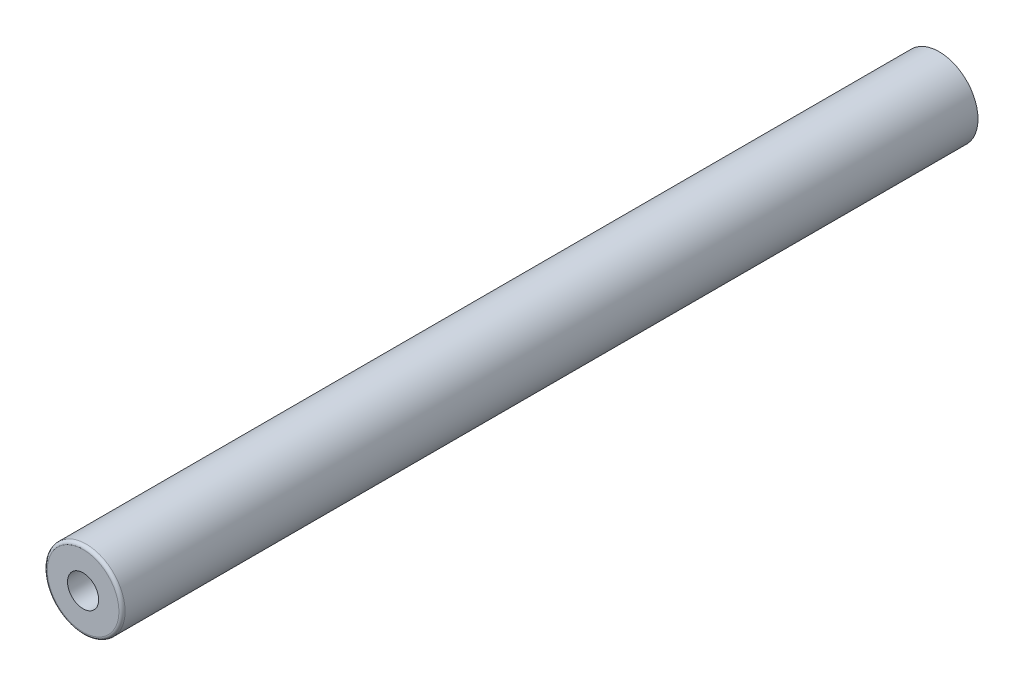
SolidWorks part; units mm, degrees
material "AISI 4130 Steel, normalized at 870C"
ref_plane "Front Plane" through (0, 0, 0) normal (1, 0, 0) x (0, 1, 0)
ref_plane "Top Plane" through (0, 0, 0) normal (0, 0, 1) x (0, 1, 0)
ref_plane "Right Plane" through (0, 0, 0) normal (0, 1, 0) x (-1, 0, 0)
sketch "Sketch1" plane through (0, 0, 0) normal (1, 0, 0) x (0, 1, 0)
  line L0 (0, 319.3174) -> (0, -301.3254) construction
  line L1 (-332.8603, 0) -> (362.1851, 0) construction
  line L2 (10, 275) -> (25, 275)
  line L3 (25, 275) -> (25, -275)
  line L4 (25, -275) -> (20, -275)
  line L5 (10, 235) -> (20, 235)
  line L6 (10, 275) -> (10, 235)
  line L7 (20, 235) -> (20, -275)
  point P13 (25, 0)
  dimension "D1" = 40
  dimension "D2" = 550
  dimension "D3" = 20
  dimension "D4" = 50
  dimension "D5" = 5
revolve "Revolve1" add sketch "Sketch1" angle 360 about L0
fillet "Fillet1" radius 2 1 edges at (25, 0, 275)
